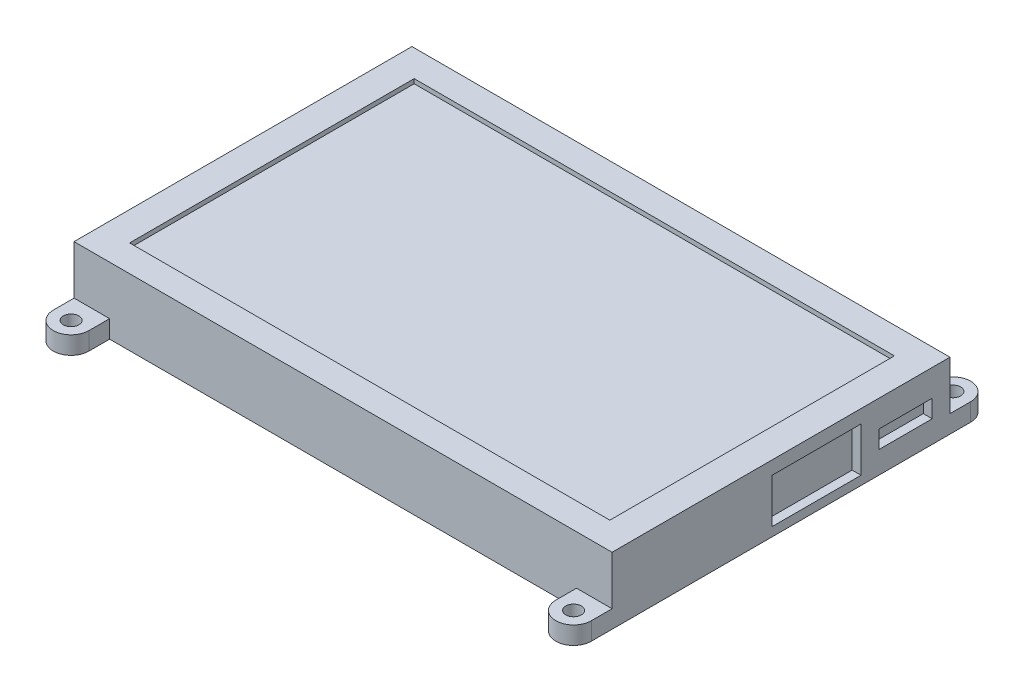
SolidWorks part; units mm, degrees
ref_plane "Front Plane" through (0, 0, 0) normal (0, 0, 1) x (1, 0, 0)
ref_plane "Top Plane" through (0, 0, 0) normal (0, 1, 0) x (1, 0, 0)
ref_plane "Right Plane" through (0, 0, 0) normal (1, 0, 0) x (0, 0, -1)
sketch "Sketch1" plane through (0, 0, 0) normal (0, 1, 0) x (1, 0, 0)
  line L1 (0, 0) -> (121, 0)
  line L2 (0, 0) -> (0, 75.99)
  line L3 (0, 75.99) -> (121, 75.99)
  line L4 (121, 0) -> (121, 75.99)
  dimension "D1" = 75.99
  dimension "D2" = 121
extrude "Boss-Extrude1" add sketch "Sketch1" along normal blind 15 contours L3 L4 L1 L2
sketch "Sketch2" plane through (0, 15, 0) normal (0, 1, 0) x (1, 0, 0)
  line L0 (60.5, 75.99) -> (60.5, 0) construction
  line L1 (0, 75.99) -> (121, 75.99) construction
  line L2 (0, 0) -> (121, 0) construction
  line L3 (0, 37.995) -> (121, 37.995) construction
  line L4 (0, 0) -> (0, 75.99) construction
  line L5 (121, 0) -> (121, 75.99) construction
  line L7 (6.5, 69.995) -> (114.5, 69.995)
  line L8 (6.5, 69.995) -> (6.5, 5.995)
  line L9 (6.5, 5.995) -> (114.5, 5.995)
  line L10 (114.5, 69.995) -> (114.5, 5.995)
  line L11 (6.5, 69.995) -> (114.5, 5.995) construction
  line L12 (6.5, 5.995) -> (114.5, 69.995) construction
  point P12 (60.5, 37.995)
  dimension "D1" = 108
  dimension "D2" = 64
extrude "Cut-Extrude1" cut sketch "Sketch2" against normal blind 1
sketch "Sketch3" plane through (0, 0, 0) normal (0, -1, 0) x (1, 0, 0)
  line L0 (4, -80.65) -> (4, -71.33) construction
  line L1 (0, -80.65) -> (0, -71.33)
  line L2 (8, -80.65) -> (8, -71.33)
  line L3 (0, -75.99) -> (121, -75.99) construction
  line L4 (60.5, -75.99) -> (60.5, 9.2683) construction
  line L5 (121, -37.995) -> (0, -37.995) construction
  line L6 (121, 0) -> (121, -75.99) construction
  line L7 (0, 0) -> (0, -75.99) construction
  line L8 (117, -80.65) -> (117, -71.33) construction
  line L9 (121, -80.65) -> (121, -71.33)
  line L10 (113, -80.65) -> (113, -71.33)
  line L11 (4, 4.66) -> (4, -4.66) construction
  line L12 (0, 4.66) -> (0, -4.66)
  line L13 (8, 4.66) -> (8, -4.66)
  line L14 (117, 4.66) -> (117, -4.66) construction
  line L15 (121, 4.66) -> (121, -4.66)
  line L16 (113, 4.66) -> (113, -4.66)
  arc A0 (0, -80.65) -> (8, -80.65) centre (4, -80.65) ccw
  arc A1 (8, -71.33) -> (0, -71.33) centre (4, -71.33) ccw
  arc A2 (121, -80.65) -> (113, -80.65) centre (117, -80.65) cw
  arc A3 (113, -71.33) -> (121, -71.33) centre (117, -71.33) cw
  arc A4 (0, 4.66) -> (8, 4.66) centre (4, 4.66) cw
  arc A5 (8, -4.66) -> (0, -4.66) centre (4, -4.66) cw
  arc A6 (121, 4.66) -> (113, 4.66) centre (117, 4.66) ccw
  arc A7 (113, -4.66) -> (121, -4.66) centre (117, -4.66) ccw
  point P2 (4, -75.99)
  point P7 (0, -75.99)
  point P8 (4, -84.65)
  point P22 (117, -75.99)
  point P29 (4, 0)
  point P36 (117, 0)
  dimension "D1" = 8.66
  dimension "D2" = 8
extrude "Boss-Extrude2" add sketch "Sketch3" against normal blind 4
sketch "Sketch4" plane through (0, 0, 0) normal (0, -1, 0) x (1, 0, 0)
  line L0 (60.5, -75.99) -> (60.5, 0) construction
  line L1 (8, -75.99) -> (113, -75.99) construction
  line L2 (8, 0) -> (113, 0) construction
  line L3 (121, -37.995) -> (0, -37.995) construction
  line L4 (121, 4.66) -> (121, -80.65) construction
  line L5 (0, 4.66) -> (0, -80.65) construction
  circle A0 centre (4, -80.65) radius 1.75
  circle A1 centre (117, -80.65) radius 1.75
  circle A2 centre (4, 4.66) radius 1.75
  circle A3 centre (117, 4.66) radius 1.75
  dimension "D1" = 3.5
extrude "Cut-Extrude3" cut sketch "Sketch4" against normal blind 4 contours A1 | A3 | A2 | A0
sketch "Sketch5" plane through (121, 0, 0) normal (1, 0, 0) x (0, 0, -1)
  line L0 (75.99, 15) -> (75.99, 4) construction
  line L1 (71.99, 9) -> (59.99, 9)
  line L2 (71.99, 9) -> (71.99, 5)
  line L3 (71.99, 5) -> (59.99, 5)
  line L4 (59.99, 9) -> (59.99, 5)
  line L5 (71.99, 9) -> (59.99, 5) construction
  line L6 (71.99, 5) -> (59.99, 9) construction
  line L7 (55.99, 12) -> (35.99, 12)
  line L8 (55.99, 12) -> (55.99, 2)
  line L9 (55.99, 2) -> (35.99, 2)
  line L10 (35.99, 12) -> (35.99, 2)
  line L11 (55.99, 12) -> (35.99, 2) construction
  line L12 (55.99, 2) -> (35.99, 12) construction
  line L13 (-4.66, 0) -> (80.65, 0) construction
  point P0 (65.99, 7)
  point P5 (45.99, 7)
  point P14 (71.99, 7)
  dimension "D1" = 20
  dimension "D2" = 10
  dimension "D3" = 20
  dimension "D4" = 2
  dimension "D5" = 12
  dimension "D6" = 4
  dimension "D7" = 4
  dimension "D8" = 5
extrude "Cut-Extrude4" cut sketch "Sketch5" against normal blind 2
